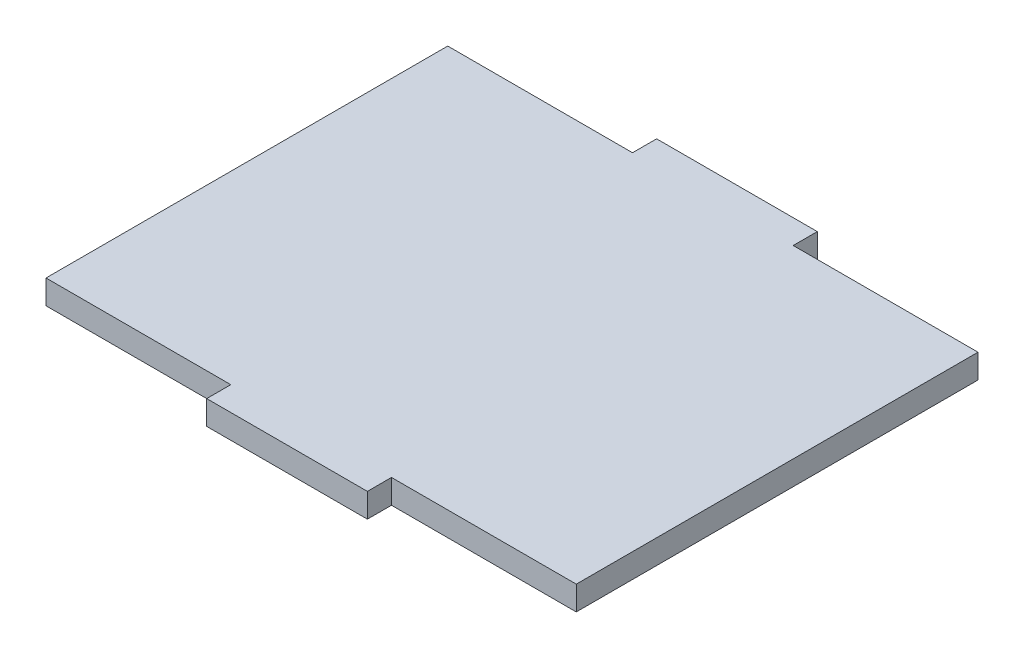
SolidWorks part; units mm, degrees
ref_plane "Front Plane" through (0, 0, 0) normal (0, 0, 1) x (1, 0, 0)
ref_plane "Top Plane" through (0, 0, 0) normal (0, 1, 0) x (1, 0, 0)
ref_plane "Right Plane" through (0, 0, 0) normal (1, 0, 0) x (0, 0, -1)
sketch "Sketch1" plane through (0, 0, 0) normal (0, 1, 0) x (1, 0, 0)
  line L0 (0, 50) -> (23, 50) construction
  line L1 (0, 0) -> (23, 0)
  line L2 (0, 0) -> (0, 50)
  line L3 (0, 50) -> (23, 50)
  line L4 (66, 0) -> (66, 50)
  line L5 (43, 50) -> (66, 50) construction
  line L7 (23, 50) -> (23, 53)
  line L8 (23, 53) -> (43, 53)
  line L9 (43, 50) -> (43, 53)
  line L10 (43, 50) -> (66, 50)
  line L11 (23, 50) -> (43, 50) construction
  line L12 (0, 50) -> (66, 50) construction
  line L13 (0, 25) -> (66, 25) construction
  line L14 (43, 0) -> (43, -3)
  line L15 (23, -3) -> (43, -3)
  line L16 (23, 0) -> (23, -3)
  line L17 (43, 0) -> (66, 0)
  point P9 (33, 50)
  dimension "D1" = 50
  dimension "D2" = 66
  dimension "D3" = 20
  dimension "D4" = 3
extrude "Boss-Extrude1" add sketch "Sketch1" along normal blind 3
